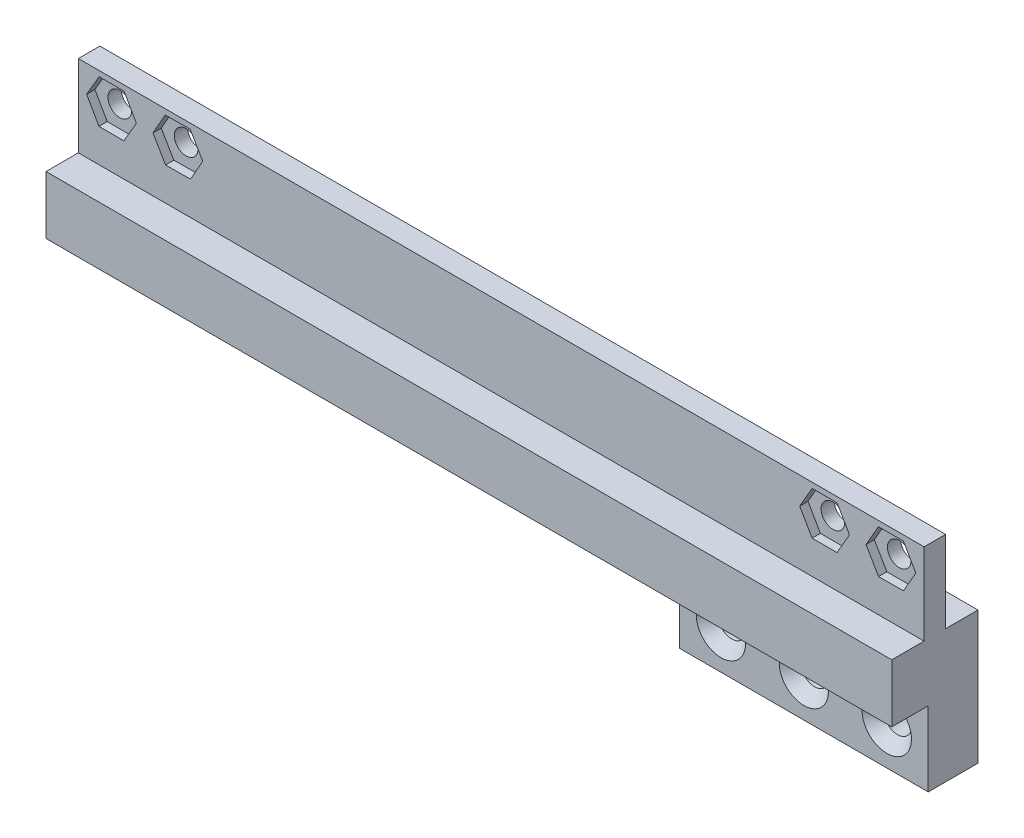
SolidWorks part; units mm, degrees
ref_plane "前视基准面" through (0, 0, 0) normal (0, 0, 1) x (1, 0, 0)
ref_plane "上视基准面" through (0, 0, 0) normal (0, 1, 0) x (1, 0, 0)
ref_plane "右视基准面" through (0, 0, 0) normal (1, 0, 0) x (0, 0, -1)
sketch "草图1" plane through (0, 0, 0) normal (0, 1, 0) x (1, 0, 0)
  line L1 (0, 0) -> (103.5, 0)
  line L2 (0, 0) -> (0, -10.4)
  line L3 (0, -10.4) -> (103.5, -10.4)
  line L4 (103.5, 0) -> (103.5, -10.4)
  dimension "D1" = 10.4
  dimension "D2" = 103.5
extrude "Base" add sketch "草图1" along normal blind 7
ref_plane "基准面1" through (0, 0, 0) normal (0, -1, 0) x (-1, 0, 0)
sketch "草图3" plane through (0, 0, 0) normal (0, -1, 0) x (-1, 0, 0)
  line L1 (-103.5, 0) -> (-73.5, 0)
  line L2 (-103.5, 0) -> (-103.5, -6)
  line L3 (-103.5, -6) -> (-73.5, -6)
  line L4 (-73.5, 0) -> (-73.5, -6)
  dimension "D1" = 30
  dimension "D2" = 6
extrude "Finger_Connector" add sketch "草图3" along normal blind 9 contours L3 L4 L1 L2
ref_plane "基准面2" through (0, 7, 0) normal (0, 1, 0) x (1, 0, 0)
sketch "草图5" plane through (0, 7, 0) normal (0, 1, 0) x (1, 0, 0)
  line L0 (0, 0) -> (0, -10.4) construction
  line L1 (0, -3.9) -> (103.5, -3.9)
  line L2 (0, -3.9) -> (0, -6.5)
  line L3 (0, -6.5) -> (103.5, -6.5)
  line L4 (103.5, -3.9) -> (103.5, -6.5)
  line L5 (103.5, -10.4) -> (103.5, 0) construction
  line L7 (0, -10.4) -> (103.5, -10.4) construction
  dimension "D1" = 3.9
  dimension "D2" = 2.6
extrude "Gear Connector" add sketch "草图5" along normal blind 9.85
ref_plane "基准面3" through (0, 0, 0) normal (-1, 0, 0) x (0, 0, 1)
sketch "草图6" plane through (0, 0, 0) normal (-1, 0, 0) x (0, 0, 1)
  line L0 (3.9, 16.85) -> (3.9, 7)
  line L1 (3.9, 7) -> (0, 7)
  line L2 (0, 7) -> (0, 0)
  line L3 (0, 0) -> (10.4, 0)
  line L4 (10.4, 0) -> (10.4, 7)
  line L5 (10.4, 7) -> (6.5, 7)
  line L6 (6.5, 7) -> (6.5, 16.85)
  line L7 (6.5, 16.85) -> (3.9, 16.85)
extrude "切除-拉伸1" cut sketch "草图6" against normal blind 1.5
ref_plane "基准面4" through (0, 0, 6) normal (0, 0, 1) x (1, 0, 0)
sketch "草图7" plane through (0, 0, 6) normal (0, 0, 1) x (1, 0, 0)
  line L0 (73.5, -4.5) -> (75, -4.5)
  line L1 (73.5, -9) -> (73.5, 0) construction
  line L2 (75, -4.5) -> (82, -4.5)
  line L3 (82, -4.5) -> (85, -4.5)
  line L4 (85, -4.5) -> (92, -4.5)
  line L5 (92, -4.5) -> (95, -4.5)
  line L6 (95, -4.5) -> (102, -4.5)
  circle A0 centre (78.5, -4.5) radius 1.675
  circle A1 centre (88.5, -4.5) radius 1.675
  circle A2 centre (98.5, -4.5) radius 1.675
  dimension "D1" = 3.35
  dimension "3.35" = 3.35
  dimension "D3" = 3.35
extrude "Finger_Connecting_Hole" [suppressed] cut sketch "草图7" against normal through all contours A0 | A1 | A2
chamfer "倒角1" [suppressed] distance 1.3 angle 45
ref_plane "基准面5" through (0, 0, 6.5) normal (0, 0, 1) x (1, 0, 0)
sketch "草图9" plane through (0, 0, 6.5) normal (0, 0, 1) x (1, 0, 0)
  line L0 (1.5, 16.85) -> (103.5, 16.85) construction
  line L2 (1.5, 7) -> (1.5, 16.85) construction
  line L3 (103.5, 16.85) -> (103.5, 7) construction
  circle A0 centre (4.6, 13.6) radius 1.425
  circle A1 centre (98.5, 13.6) radius 1.425
  dimension "D1" = 2.85
  dimension "D2" = 2.85
  dimension "D3" = 3.25
  dimension "D4" = 3.1
  dimension "D5" = 3.25
  dimension "D6" = 5
extrude "切除-拉伸3" [suppressed] cut sketch "草图9" against normal through all
sketch "草图10" plane through (0, 0, 0) normal (0, 1, 0) x (1, 0, 0)
  line L0 (1.5, 0) -> (1.5, -10.4)
fillet "圆角2" [suppressed] radius 1
fillet "圆角3" [suppressed] radius 1
ref_plane "基准面6" through (0, 0, 6.5) normal (0, 0, 1) x (1, 0, 0)
sketch "草图20" plane through (0, 0, 6.5) normal (0, 0, 1) x (1, 0, 0)
  line L0 (1.5, 16.85) -> (1.5, 10.35)
  line L1 (1.5, 7) -> (1.5, 16.85) construction
  line L2 (1.5, 10.35) -> (103.5, 10.35)
  line L3 (103.5, 16.85) -> (103.5, 7) construction
  line L4 (103.5, 10.35) -> (103.5, 16.85)
  line L5 (103.5, 16.85) -> (1.5, 16.85)
  line L8 (22.5, 10.35) -> (17.5, 10.35)
  line L9 (17.5, 10.35) -> (9.5, 10.35)
  line L10 (9.5, 10.35) -> (1.5, 10.35)
  line L11 (9.5, 10.35) -> (9.5, 16.85)
  line L12 (9.5, 16.85) -> (1.5, 10.35)
  line L13 (9.5, 16.85) -> (17.5, 10.35)
  line L15 (103.5, 10.35) -> (95.5, 10.35)
  line L16 (95.5, 10.35) -> (87.5, 10.35)
  line L17 (87.5, 10.35) -> (87.5, 16.85)
  line L18 (87.5, 16.85) -> (95.5, 10.35)
  line L19 (103.5, 16.85) -> (95.5, 10.35)
  circle A1 centre (13.5, 13.6) radius 1.425
  circle A2 centre (5.5, 13.6) radius 1.425
  circle A3 centre (99.5, 13.6) radius 1.425
  circle A4 centre (91.5, 13.6) radius 1.425
  dimension "D1" = 2.85
  dimension "D5" = 2.85
  dimension "D6" = 2.85
  dimension "D7" = 2.85
  dimension "D2" = 8
  dimension "D3" = 4
  dimension "D4" = 8
extrude "切除-拉伸4" cut sketch "草图20" against normal through all
sketch "草图22" plane through (0, 0, 6.5) normal (0, 0, 1) x (1, 0, 0)
  line L7 (92.9986, 10.9985) -> (94.5022, 13.5971)
  line L8 (94.5022, 13.5971) -> (93.0036, 16.1985)
  line L9 (93.0036, 16.1985) -> (90.0014, 16.2015)
  line L10 (90.0014, 16.2015) -> (88.4978, 13.6029)
  line L11 (88.4978, 13.6029) -> (89.9964, 11.0015)
  line L12 (89.9964, 11.0015) -> (92.9986, 10.9985)
  line L13 (101.01, 11.0052) -> (102.5022, 13.6103)
  line L14 (102.5022, 13.6103) -> (100.9922, 16.2051)
  line L15 (100.9922, 16.2051) -> (97.99, 16.1948)
  line L16 (97.99, 16.1948) -> (96.4978, 13.5897)
  line L17 (96.4978, 13.5897) -> (98.0078, 10.9949)
  line L18 (98.0078, 10.9949) -> (101.01, 11.0052)
  line L19 (15.024, 11.0133) -> (16.5021, 13.6265)
  line L20 (16.5021, 13.6265) -> (14.9781, 16.2131)
  line L21 (14.9781, 16.2131) -> (11.976, 16.1867)
  line L22 (11.976, 16.1867) -> (10.4979, 13.5735)
  line L23 (10.4979, 13.5735) -> (12.0219, 10.9869)
  line L24 (12.0219, 10.9869) -> (15.024, 11.0133)
  line L25 (6.9852, 10.9909) -> (8.5022, 13.5817)
  line L26 (8.5022, 13.5817) -> (7.017, 16.1908)
  line L27 (7.017, 16.1908) -> (4.0148, 16.2091)
  line L28 (4.0148, 16.2091) -> (2.4978, 13.6183)
  line L29 (2.4978, 13.6183) -> (3.983, 11.0092)
  line L30 (3.983, 11.0092) -> (6.9852, 10.9909)
  circle A1 centre (91.5, 13.6) radius 1.425
  circle A2 centre (91.5, 13.6) radius 2.6 construction
  circle A3 centre (99.5, 13.6) radius 2.6 construction
  circle A4 centre (99.5, 13.6) radius 1.425
  circle A5 centre (13.5, 13.6) radius 1.425
  circle A6 centre (5.5, 13.6) radius 1.425
  circle A7 centre (13.5, 13.6) radius 2.6 construction
  circle A8 centre (5.5, 13.6) radius 2.6 construction
  dimension "D1" = 5.2
  dimension "D3" = 5.2
  dimension "D2" = 5.2
  dimension "D4" = 5.2
extrude "切除-拉伸5" cut sketch "草图22" against normal blind 1
fillet "圆角4" [suppressed] radius 1
fillet "圆角5" [suppressed] radius 1
fillet "圆角6" [suppressed] radius 1
fillet "圆角8" [suppressed] radius 1
sketch "草图27" plane through (0, 0, 6) normal (0, 0, 1) x (1, 0, 0)
  line L0 (73.5, 0) -> (73.5, -9)
  line L1 (73.5, -9) -> (103.5, -9)
  line L2 (103.5, -9) -> (103.5, 0)
  line L3 (103.5, 0) -> (73.5, 0)
  line L4 (73.5, -4.5) -> (103.5, -4.5)
  line L5 (73.5, -4.5) -> (83.5, -4.5)
  line L6 (83.5, -4.5) -> (93.5, -4.5)
  line L7 (93.5, -4.5) -> (103.5, -4.5)
  line L8 (73.5, -4.5) -> (83.5, -4.5)
  circle A0 centre (98.5, -4.5) radius 1.675
  circle A1 centre (88.5, -4.5) radius 1.675
  circle A2 centre (78.5, -4.5) radius 1.675
  dimension "D1" = 3.35
  dimension "D2" = 3.35
  dimension "D3" = 3.35
extrude "切除-拉伸6" cut sketch "草图27" against normal blind 10 contours A2 | A1 | A0
chamfer "倒角2" distance 1.3 angle 45 3 edges at (80.175, -4.5, 6) (90.175, -4.5, 6) (100.175, -4.5, 6)
